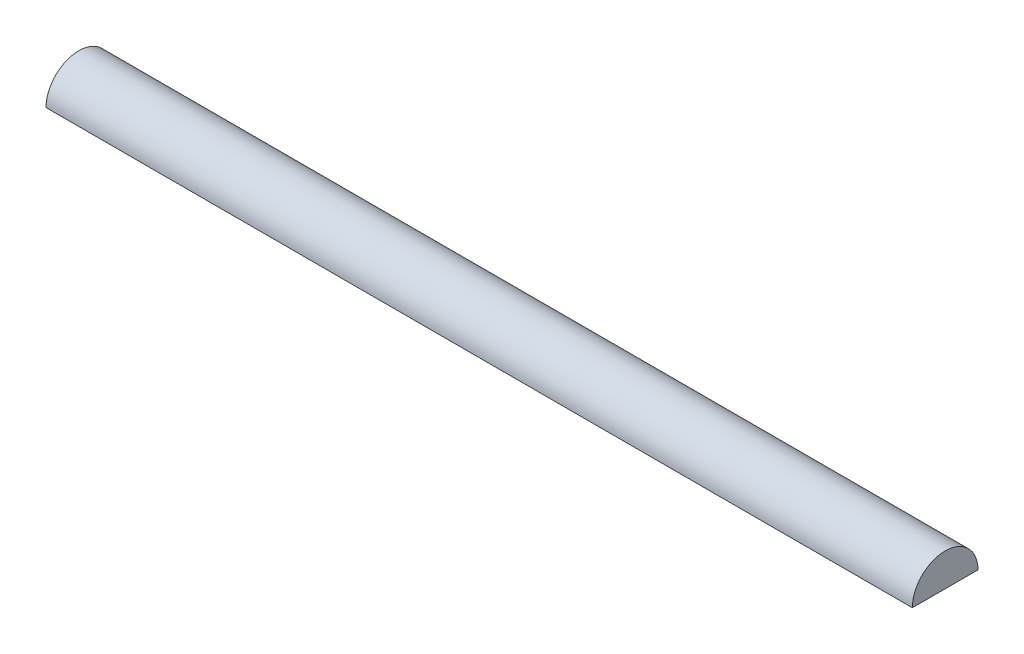
SolidWorks part; units mm, degrees
ref_plane "Front Plane" through (0, 0, 0) normal (0, 0, 1) x (1, 0, 0)
ref_plane "Top Plane" through (0, 0, 0) normal (0, 1, 0) x (1, 0, 0)
ref_plane "Right Plane" through (0, 0, 0) normal (1, 0, 0) x (0, 0, -1)
sketch "Sketch1" plane through (0, 0, 0) normal (0, 1, 0) x (-1, 0, 0)
  line L0 (2668.016, 619.3759) -> (1757.185, 174.7685)
  line L1 (1757.185, 174.7685) -> (2679.162, 350)
  line L2 (2679.162, 350) -> (2679.162, 0)
  line L3 (2679.162, 0) -> (5679.162, 0)
  line L4 (5679.162, 0) -> (5679.162, 497.0129)
  line L5 (6405.6089, 619.3759) -> (6957.8511, 497.0129)
  line L6 (6957.8511, 497.0129) -> (5679.162, 497.0129)
  line L7 (6405.6089, 619.3759) -> (2668.016, 619.3759)
  dimension "D1" = 350
  dimension "D3" = 3000
revolve "Revolve1" add sketch "Sketch1" angle 360 about L3
sketch "Sketch2" plane through (0, 0, 0) normal (1, 0, 0) x (0, 0, -1)
  circle A0 centre (0, 0) radius 757.9974
extrude "Boss-Extrude1" add sketch "Sketch2" along normal blind 5000 and the other way blind 15000 separate body
combine bodies "Combine1" operation type subtract main body 102 bodies to subtract 101
sketch "Sketch3" plane through (0, 0, 0) normal (0, 1, 0) x (-1, 0, 0)
  line L1 (-6326.4254, 2080.3524) -> (16656.2112, 2080.3524)
  line L2 (-6326.4254, 2080.3524) -> (-6326.4254, -1559.5909)
  line L3 (-6326.4254, -1559.5909) -> (16656.2112, -1559.5909)
  line L4 (16656.2112, 2080.3524) -> (16656.2112, -1559.5909)
extrude "Cut-Extrude1" cut sketch "Sketch3" against normal through all
